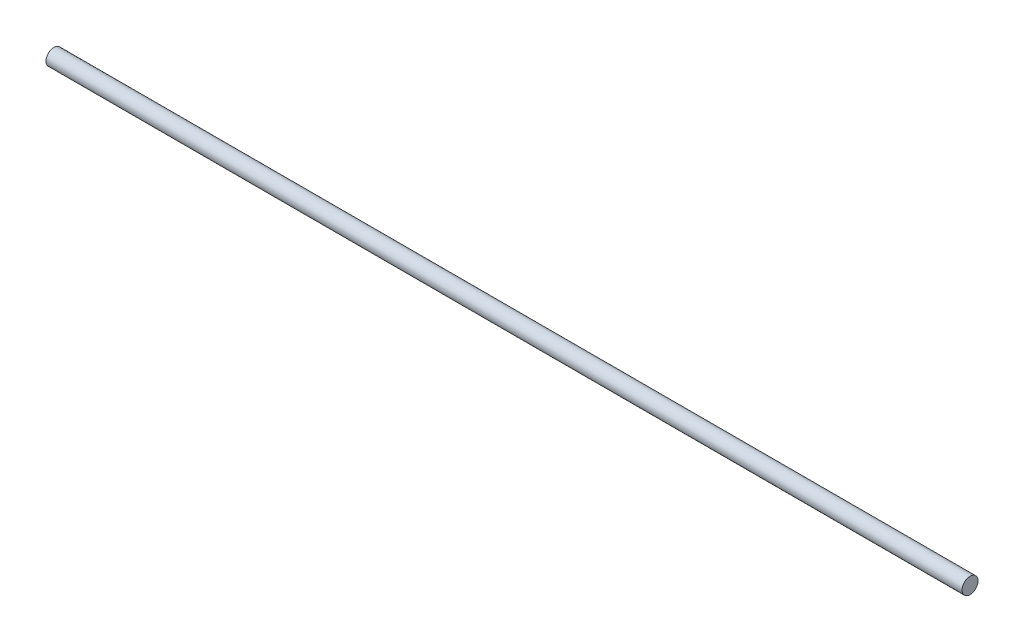
SolidWorks part; units mm, degrees
ref_plane "Front Plane" through (0, 0, 0) normal (0, 0, 1) x (1, 0, 0)
ref_plane "Top Plane" through (0, 0, 0) normal (0, 1, 0) x (1, 0, 0)
ref_plane "Right Plane" through (0, 0, 0) normal (1, 0, 0) x (0, 0, -1)
sketch "Sketch1" plane through (0, 0, 0) normal (1, 0, 0) x (0, 0, -1)
  circle A0 centre (0, 0) radius 4
  dimension "D1" = 8
extrude "Boss-Extrude1" add sketch "Sketch1" along normal blind 460
